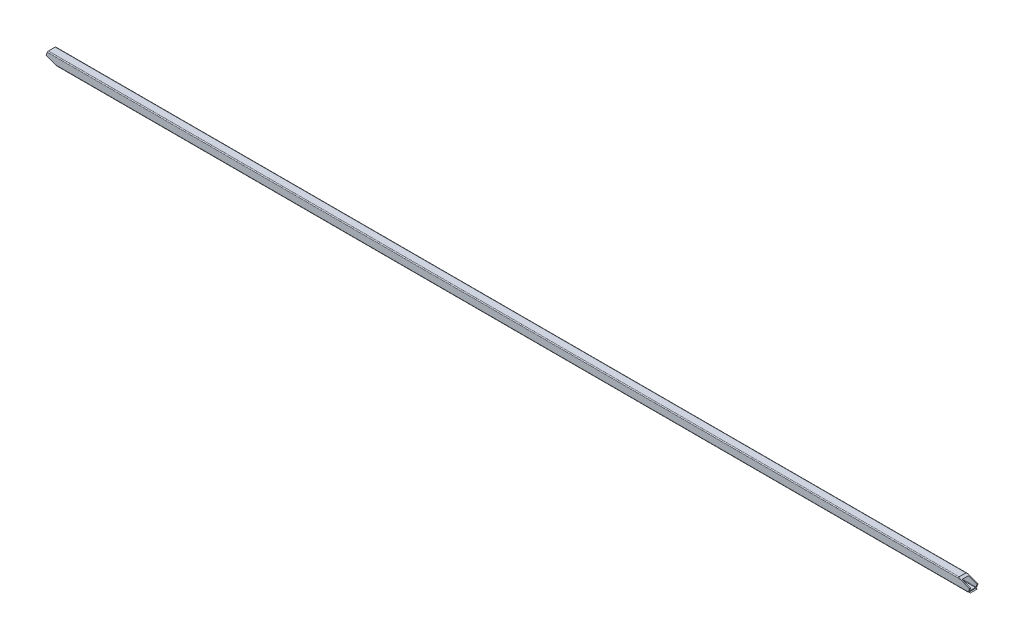
SolidWorks part; units mm, degrees
ref_plane "Front Plane" through (0, 0, 0) normal (0, 0, 1) x (1, 0, 0)
ref_plane "Top Plane" through (0, 0, 0) normal (0, 1, 0) x (1, 0, 0)
ref_plane "Right Plane" through (0, 0, 0) normal (1, 0, 0) x (0, 0, -1)
sketch "Sketch3" plane through (0, 0, 0) normal (1, 0, 0) x (0, 0, -1)
  line L1 (-12.7, 12.7) -> (12.7, 12.7)
  line L2 (-12.7, 12.7) -> (-12.7, -12.7)
  line L3 (-12.7, -12.7) -> (12.7, -12.7)
  line L4 (12.7, 12.7) -> (12.7, -12.7)
  line L5 (-12.7, 12.7) -> (12.7, -12.7) construction
  line L6 (-12.7, -12.7) -> (12.7, 12.7) construction
  line L7 (-9.652, -9.652) -> (9.652, -9.652)
  line L8 (-9.652, -9.652) -> (-9.652, 9.652)
  line L9 (-9.652, 9.652) -> (9.652, 9.652)
  line L10 (9.652, -9.652) -> (9.652, 9.652)
  line L11 (-9.652, -9.652) -> (9.652, 9.652) construction
  line L12 (-9.652, 9.652) -> (9.652, -9.652) construction
  point P0 (0, 0)
  point P6 (0, 0)
  dimension "D1" = 25.4
  dimension "D2" = 19.304
  dimension "D3" = 19.304
  dimension "D4" = 25.4
extrude "Boss-Extrude1" add sketch "Sketch3" against normal blind 2786.03
fillet "Fillet1" radius 2.5 4 edges at (-1393.015, -12.7, -12.7) (-1393.015, -12.7, 12.7) (-1393.015, 12.7, -12.7) (-1393.015, 12.7, 12.7)
fillet "Fillet2" radius 1 4 edges at (-1393.015, -9.652, -9.652) (-1393.015, 9.652, -9.652) (-1393.015, 9.652, 9.652) (-1393.015, -9.652, 9.652)
sketch "Sketch4" plane through (0, 0, 12.7) normal (0, 0, 1) x (1, 0, 0)
  line L0 (-2786.03, -12.7) -> (-2786.03, 0.0158)
  line L1 (-2786.03, 10.2) -> (-2786.03, -10.2) construction
  line L2 (-2786.03, 0.0158) -> (-2752.02, -12.7)
  line L3 (0, -12.7) -> (-2786.03, -12.7) construction
  line L4 (-2752.02, -12.7) -> (-2786.03, -12.7)
  line L5 (-2786.03, 12.7) -> (-2786.03, 0.0158)
  line L6 (-2786.03, 0.0158) -> (-2781.2876, 12.7)
  line L7 (-2786.03, 12.7) -> (0, 12.7) construction
  line L8 (-2781.2876, 12.7) -> (-2786.03, 12.7)
  line L9 (0, 10.2) -> (-2786.03, 10.2) construction
  line L10 (-1393.015, 10.2) -> (-1393.015, -10.2) construction
  line L11 (-2786.03, -10.2) -> (0, -10.2) construction
  line L12 (0, -12.7) -> (0, 0.0158)
  line L13 (0, -12.7) -> (0, 12.7316)
  line L14 (0, 12.7316) -> (0, 0.1231)
  line L15 (0, 12.7) -> (0, -12.6684)
  line L16 (-34.01, 12.7316) -> (0, 12.7316)
  line L18 (0, 0.0158) -> (-59.3903, 0.0158) construction
  line L19 (-34.01, 12.7316) -> (0, 12.7316)
  line L20 (0, 0.0158) -> (-34.01, 12.7316)
  line L21 (-4.656, -12.7) -> (0, -12.6684)
  line L22 (0, 0.0158) -> (-4.656, -12.7)
  point P23 (-4.7056, -12.0789)
  point P29 (-4.7423, -12.7)
  point P30 (-5.4228, -12.7)
  line M19 (-2786.03, 10.2) -> (-2786.03, -10.2)
  line M20 (-2786.03, -10.2) -> (0, -10.2)
  line M21 (0, -10.2) -> (0, 10.2)
  line M22 (0, 10.2) -> (-2786.03, 10.2)
  dimension "D1" = 20.5
  dimension "D2" = 34.01
  dimension "D3" = 69.5
  dimension "D4" = 20.5
  dimension "D5" = 69.5
extrude "Cut-Extrude1" cut sketch "Sketch4" against normal through all contours L20 L13 M21 M22 | L20 L13 L14 L16 M22 | L22 M21 M20 | L22 L21 L13 M20 | L6 L8 L5 M22 | L6 M19 M22 | L2 M19 M20 | L4 L2 L0 M20
